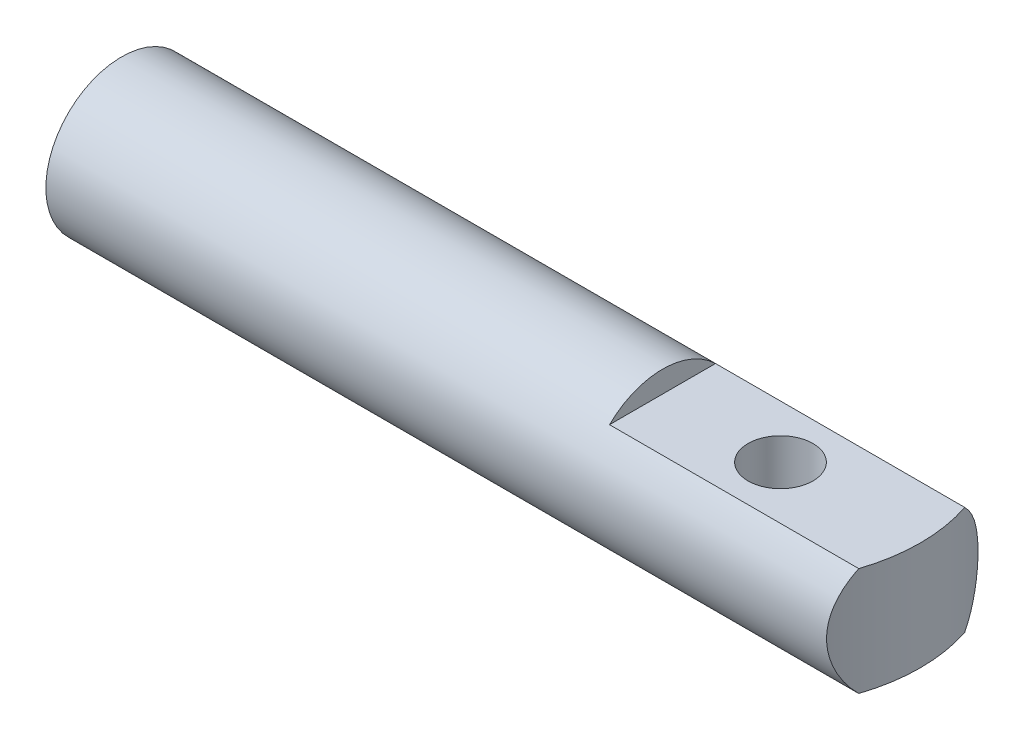
SolidWorks part; units mm, degrees
ref_plane "Front Plane" through (0, 0, 0) normal (0, 0, 1) x (1, 0, 0)
ref_plane "Top Plane" through (0, 0, 0) normal (0, 1, 0) x (1, 0, 0)
ref_plane "Right Plane" through (0, 0, 0) normal (1, 0, 0) x (0, 0, -1)
sketch "Sketch1" plane through (0, 0, 0) normal (0, 1, 0) x (1, 0, 0)
  line L0 (134.425, 0) -> (-141.075, 0) construction
  line L2 (114.475, 12) -> (14.475, 12)
  line L3 (114.475, 12) -> (114.475, 14)
  line L4 (114.475, 14) -> (14.475, 14)
  line L5 (14.475, 12) -> (14.475, 14)
  dimension "D1" = 12
  dimension "D2" = 2
  dimension "D3" = 100
revolve "Revolve1" add sketch "Sketch1" angle 360 about L0
sketch "Sketch2" plane through (114.475, 0, 0) normal (1, 0, 0) x (0, 0, -1)
  circle A0 centre (0, 0) radius 12
  dimension "D1" = 24
extrude "Boss-Extrude1" add sketch "Sketch2" against normal blind 16
sketch "Sketch3" plane through (0, 0, 0) normal (0, 1, 0) x (1, 0, 0)
  circle A0 centre (131.1382, 0) radius 31
  dimension "D1" = 62
extrude "Boss-Extrude2" add sketch "Sketch3" along normal mid plane 20 contours A0
sketch "Sketch4" plane through (14.475, 0, 0) normal (-1, 0, 0) x (0, 0, 1)
  circle A1 centre (0, 0) radius 14
  dimension "D1" = 28
extrude "Cut-Extrude1" cut sketch "Sketch4" against normal through all flip side to cut
sketch "Sketch5" plane through (0, -10, 0) normal (0, -1, 0) x (1, 0, 0)
  circle A0 centre (136.2847, 0) radius 6
  dimension "D1" = 12
extrude "Cut-Extrude2" cut sketch "Sketch5" against normal through all
sketch "Sketch6" plane through (14.475, 0, 0) normal (-1, 0, 0) x (0, 0, 1)
  circle A1 centre (0, 0) radius 12
  circle A2 centre (0, 0) radius 8
  dimension "D1" = 24
  dimension "D2" = 4
extrude "Boss-Extrude3" add sketch "Sketch6" against normal blind 2
equation "\"HOLE_DIAM\"= 2 * \"RAYON_AXE\" - 4"
equation "\"D1@Sketch5\"=\"HOLE_DIAM\""
equation "\"RAYON_AXE\"=8"
equation "\"D1@Sketch1\"=\"RAYON_AXE\"+4"
equation "\"D1@Sketch2\"=2*(\"RAYON_AXE\"+4)"
equation "\"D1@Sketch6\"=2*(\"RAYON_AXE\"+4)"
equation "\"D1@Sketch4\"=2*(\"RAYON_AXE\"+4)+4"
